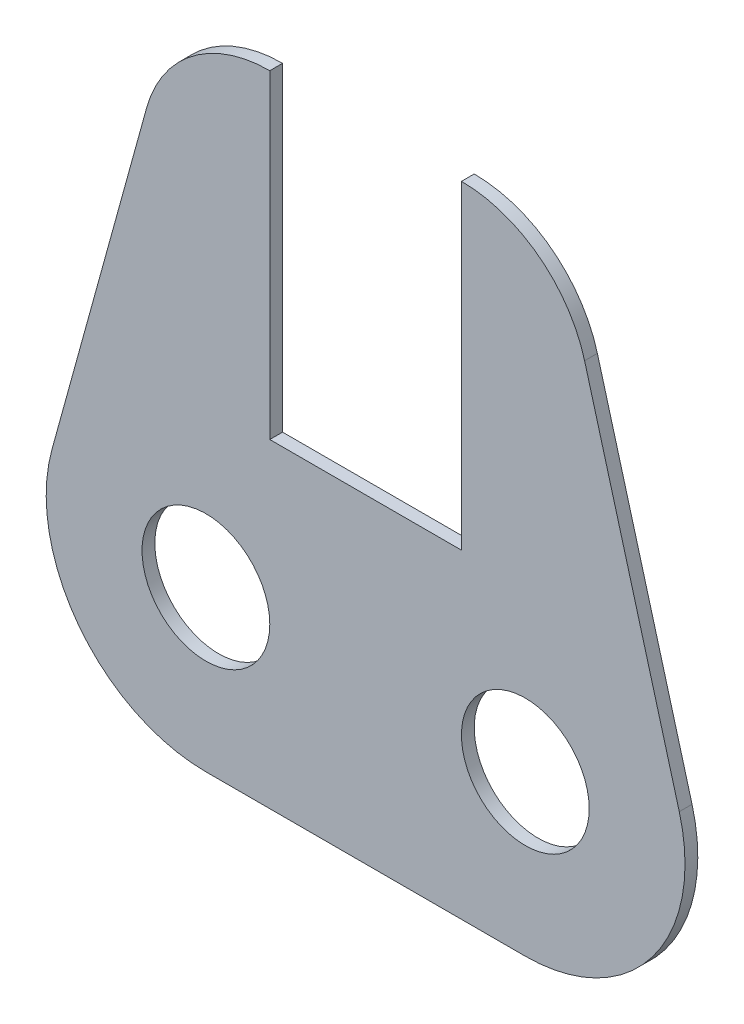
SolidWorks part; units mm, degrees
ref_plane "Ön Düzlem" through (0, 0, 0) normal (0, 0, 1) x (1, 0, 0)
ref_plane "Üst Düzlem" through (0, 0, 0) normal (0, 1, 0) x (1, 0, 0)
ref_plane "Sağ Düzlem" through (0, 0, 0) normal (1, 0, 0) x (0, 0, -1)
sketch "Çizim2" plane through (0, 0, 0) normal (0, 0, 1) x (1, 0, 0)
  line L2 (-15, 100) -> (-15, 50)
  line L3 (-15, 50) -> (15, 50)
  line L4 (15, 50) -> (15, 100)
  line L5 (-25, -0.05) -> (25, -0.05)
  line L6 (-49.0998, 31.5985) -> (-34.2798, 85.3188)
  line L7 (34.2798, 85.3188) -> (49.0998, 31.5985)
  arc A0 (-15, 100) -> (-34.2798, 85.3188) centre (-15, 80) ccw
  arc A1 (15, 100) -> (34.2798, 85.3188) centre (15, 80) cw
  arc A2 (-49.0998, 31.5985) -> (-25, -0.05) centre (-25, 24.95) ccw
  arc A3 (25, -0.05) -> (49.0998, 31.5985) centre (25, 24.95) ccw
  circle A4 centre (-25, 24.95) radius 10
  circle A5 centre (25, 24.95) radius 10
  point P6 (0, 100)
  dimension "D5" = 50
  dimension "D6" = 20
  dimension "D7" = 50
  dimension "D8" = 20
  dimension "D9" = 20
  dimension "D2" = 30
  dimension "D3" = 30
  dimension "D4" = 50
  dimension "D10" = 50
extrude "Yükseklik-Ekstrüzyon1" add sketch "Çizim2" along normal blind 2
